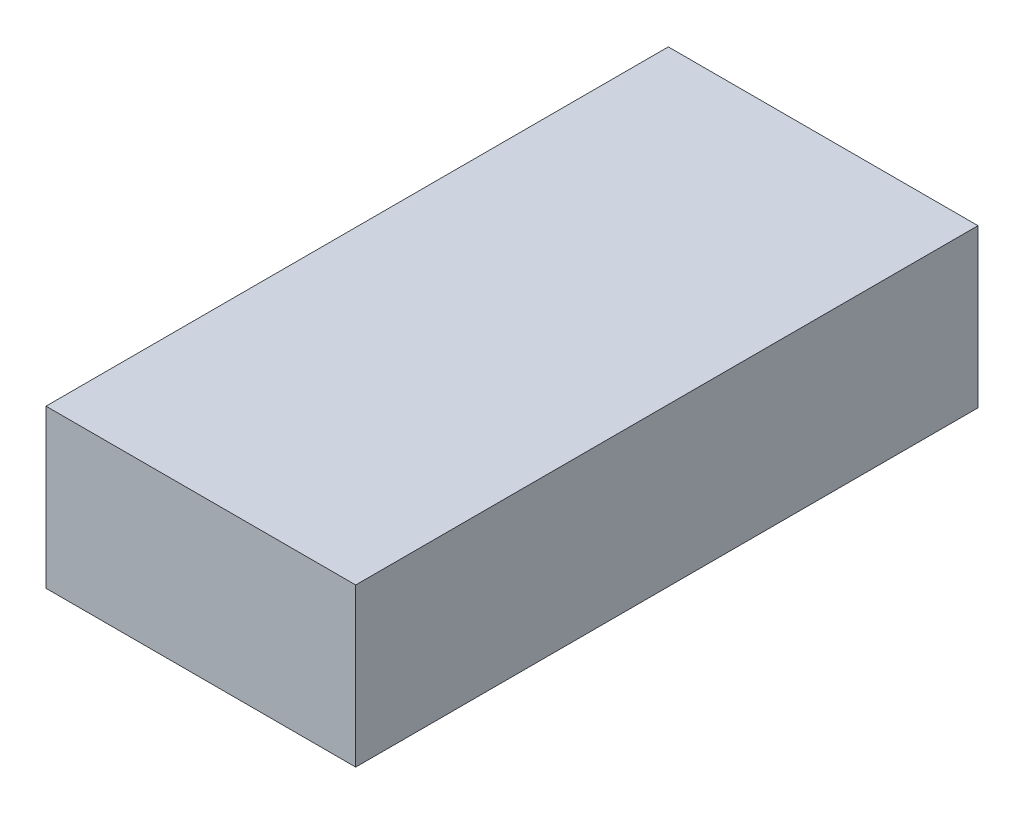
SolidWorks part; units mm, degrees
ref_plane "Front Plane" through (0, 0, 0) normal (0, 0, 1) x (1, 0, 0)
ref_plane "Top Plane" through (0, 0, 0) normal (0, 1, 0) x (1, 0, 0)
ref_plane "Right Plane" through (0, 0, 0) normal (1, 0, 0) x (0, 0, -1)
sketch "Sketch1" plane through (0, 0, 0) normal (0, 1, 0) x (1, 0, 0)
  line L1 (-53, 106.5) -> (53, 106.5)
  line L2 (-53, 106.5) -> (-53, -106.5)
  line L3 (-53, -106.5) -> (53, -106.5)
  line L4 (53, 106.5) -> (53, -106.5)
  line L5 (-53, 106.5) -> (53, -106.5) construction
  line L6 (-53, -106.5) -> (53, 106.5) construction
  point P0 (0, 0)
  dimension "D1" = 106
  dimension "D2" = 213
extrude "Boss-Extrude1" add sketch "Sketch1" along normal blind 54
